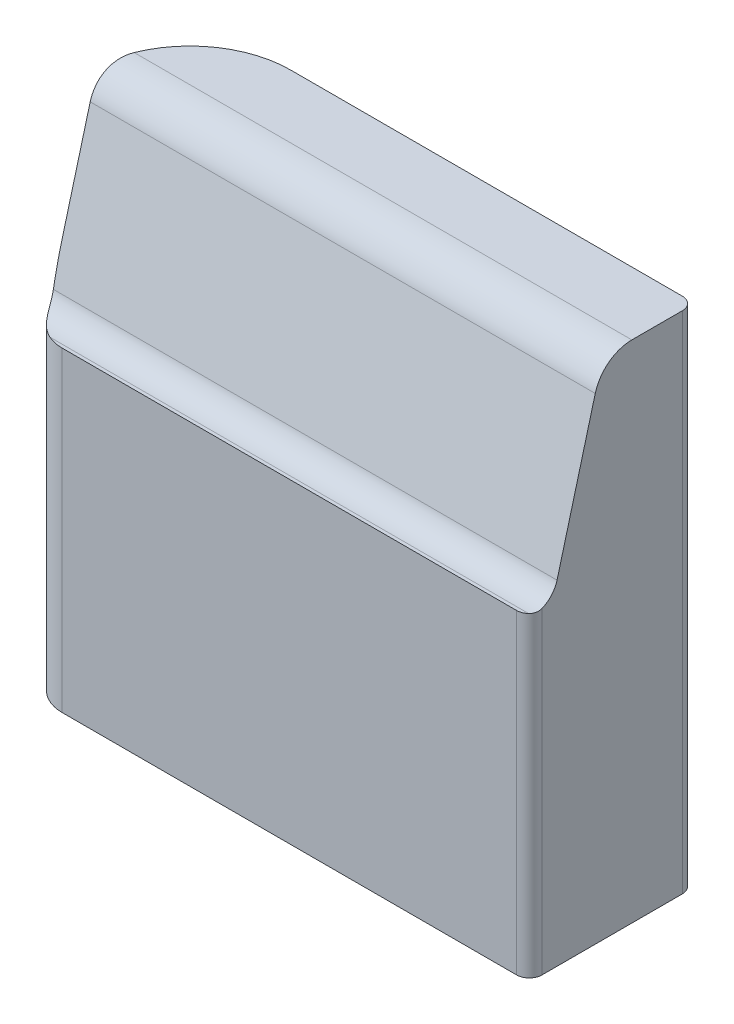
SolidWorks part; units mm, degrees
material "K110"
ref_plane "Front Plane" through (0, 0, 0) normal (0, 0, 1) x (1, 0, 0)
ref_plane "Top Plane" through (0, 0, 0) normal (0, 1, 0) x (1, 0, 0)
ref_plane "Right Plane" through (0, 0, 0) normal (1, 0, 0) x (0, 0, -1)
sketch "Sketch1" plane through (0, 0, 0) normal (1, 0, 0) x (0, 0, -1)
  line L0 (-5, 0) -> (0, 0)
  line L1 (0, 0) -> (0, -40)
  line L2 (0, -40) -> (-13.12, -40)
  line L3 (-13.12, -40) -> (-13.12, -15)
  line L4 (-13.12, -15) -> (-11.3212, -15)
  line L5 (-11.3212, -15) -> (-7.8978, -2.2235)
  arc A0 (-7.8978, -2.2235) -> (-5, 0) centre (-5, -3) cw
  dimension "D2" = 3
  dimension "D1" = 5
  dimension "D3" = 40
  dimension "D4" = 25
  dimension "D5" = 75
  dimension "D6" = 13.12
extrude "Boss-Extrude1" add sketch "Sketch1" along normal mid plane 40
fillet "Fillet1" radius 1 2 edges at (20, -20, 0) (20, -27.5, 13.12)
fillet "Fillet2" radius 2 1 edges at (0, -15, 11.3212)
fillet "Fillet3" radius 8 1 edges at (-20, -20, 0)
fillet "Fillet4" radius 3 1 edges at (-20, -27.5, 13.12)
hole_wizard "M6 Tapped Hole1" positions "Sketch4" profile "Sketch3" tap size "M6" standard "ISO"
sketch "Sketch4" plane through (0, -40, 0) normal (0, -1, 0) x (-1, 0, 0)
  line L0 (-20, -6.56) -> (19.8693, -6.56) construction
  line L1 (-20, -12.12) -> (-20, -1) construction
  arc A0 (20, -8) -> (12, 0) centre (12, -8) ccw construction
  point P0 (-13, -6.56)
  point P2 (9.8693, -6.56)
  point P14 (0, 0)
  dimension "D1" = 7
  dimension "D2" = 10
sketch "Sketch3" plane through (13, -40, 6.56) normal (1, 0, 0) x (0, 0, -1)
  line L0 (0, 0) -> (0, 16.5022)
  line L1 (0, 16.5022) -> (2.5, 15)
  line L2 (2.5, 15) -> (2.5, 0.525)
  line L3 (2.5, 0.525) -> (3.025, 0)
  line L5 (3.025, 0) -> (0, 0)
  line L6 (-2.5, 0.525) -> (-3.025, 0) construction
  line L10 (0, 16.5022) -> (-2.5, 15) construction
  line L11 (0, -6.35) -> (0, 107.95) construction
  dimension "Tap Drill Dia." = 5
  dimension "Tap Drill Depth" = 15
  dimension "Near C'Sink Dia." = 6.05
  dimension "Near C'Sink Angle" = 90
  dimension "Drill Angle" = 118
cosmetic thread "Hole Thread1"
cosmetic thread "Hole Thread2"
